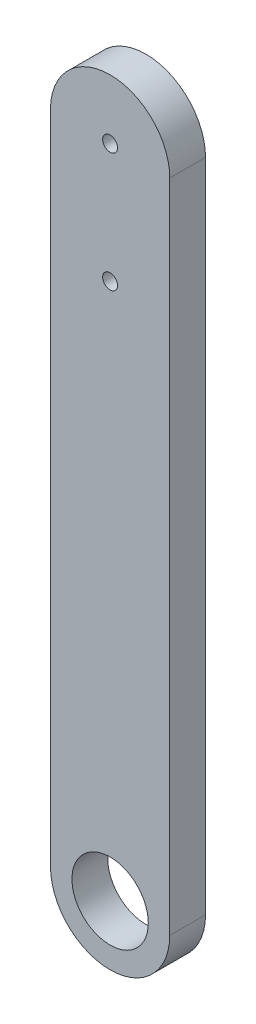
SolidWorks part; units mm, degrees
ref_plane "Plan de face" through (0, 0, 0) normal (0, 0, 1) x (1, 0, 0)
ref_plane "Plan de dessus" through (0, 0, 0) normal (0, 1, 0) x (1, 0, 0)
ref_plane "Plan de droite" through (0, 0, 0) normal (1, 0, 0) x (0, 0, -1)
sketch "Esquisse1" plane through (0, 0, 0) normal (0, 0, 1) x (1, 0, 0)
  line L3 (-69.1411, -13.7) -> (-69.1411, -33.7) construction
  line L4 (-79.1411, -13.7) -> (-79.1411, -123.7)
  line L5 (-59.1411, -123.7) -> (-59.1411, -13.7)
  line L6 (0, 0) -> (-129.4876, 0) construction
  line L7 (-129.4876, 0) -> (0, 0) construction
  line L8 (0, 0) -> (0, -104.4404) construction
  line L9 (-69.1411, -13.7) -> (-69.1411, -123.7) construction
  circle A2 centre (-69.1411, -13.7) radius 1.25
  circle A5 centre (-69.1411, -33.7) radius 1.25
  arc A10 (-79.1411, -123.7) -> (-59.1411, -123.7) centre (-69.1411, -123.7) ccw
  arc A11 (-59.1411, -13.7) -> (-79.1411, -13.7) centre (-69.1411, -13.7) ccw
  circle A12 centre (-69.1411, -123.7) radius 6.4
  point P5 (-69.1411, -33.7)
  dimension "D3" = 12.8
  dimension "D5" = 2.5
  dimension "D6" = 13.7
  dimension "D7" = 110
  dimension "D8" = 2.5
  dimension "D1" = 20
  dimension "D2" = 20
  dimension "D4" = 59.1411
extrude "Boss.-Extru.1" add sketch "Esquisse1" along normal blind 6
